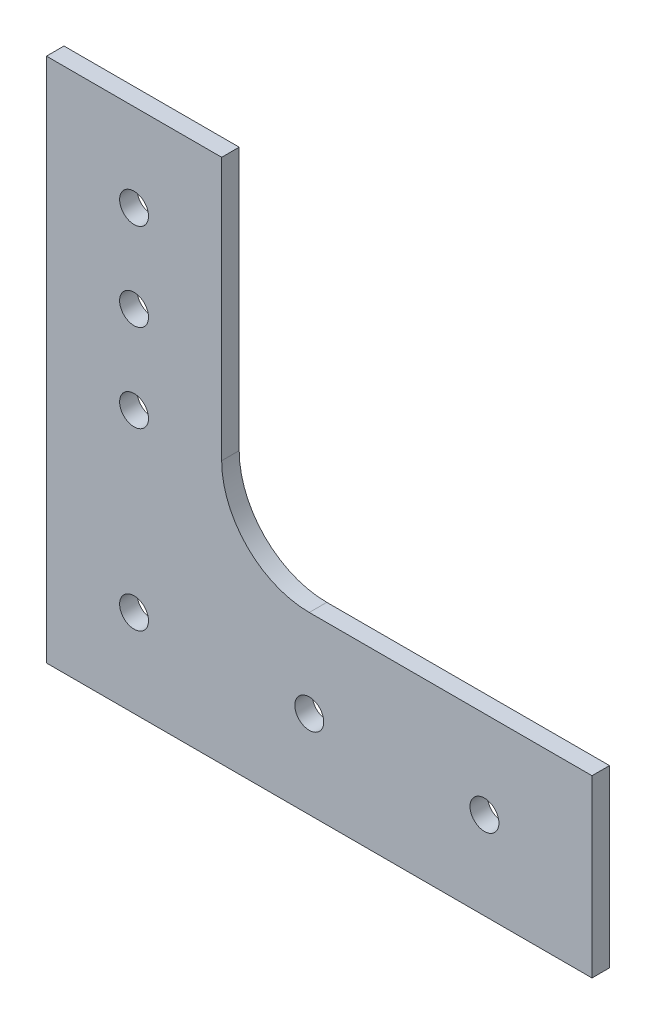
SolidWorks part; units mm, degrees
ref_plane "前视基准面" through (0, 0, 0) normal (0, 0, 1) x (1, 0, 0)
ref_plane "上视基准面" through (0, 0, 0) normal (0, 1, 0) x (1, 0, 0)
ref_plane "右视基准面" through (0, 0, 0) normal (1, 0, 0) x (0, 0, -1)
other "Configuration Table"
sketch "草图1" plane through (0, 0, 0) normal (0, 0, 1) x (1, 0, 0)
  line L0 (10, 10) -> (52.2764, 10)
  line L1 (-10, -10) -> (52.2764, -10)
  line L4 (52.2764, -10) -> (52.2764, 10)
  line L5 (-1.5653, -0.5218) -> (1.5653, 0.5218) construction
  line L6 (-1.5653, 0.5218) -> (1.5653, -0.5218) construction
  line L8 (-10, 10) -> (-10, 50)
  line L9 (-10, 50) -> (10, 50)
  line L10 (10, 10) -> (10, 50)
  line L11 (-10, 10) -> (-10, -10)
  circle A2 centre (20, 0) radius 1.65
  circle A3 centre (0, 20) radius 1.65
  circle A5 centre (0, 40) radius 1.65
  circle A6 centre (0, 30) radius 1.65
  circle A9 centre (0, 0) radius 1.65
  circle A10 centre (40, 0) radius 1.65
  point P0 (0, 0)
  dimension "D11" = 10
  dimension "D9" = 3.3
  dimension "D12" = 10
  dimension "D3" = 3.3
  dimension "D4" = 3.3
  dimension "D2" = 20
  dimension "D5" = 20
  dimension "D6" = 20
  dimension "D7" = 20
  dimension "D8" = 20
  dimension "D10" = 40
extrude "凸台-拉伸1" add sketch "草图1" along normal blind 2
fillet "圆角1" radius 10 1 edges at (10, 10, 1)
